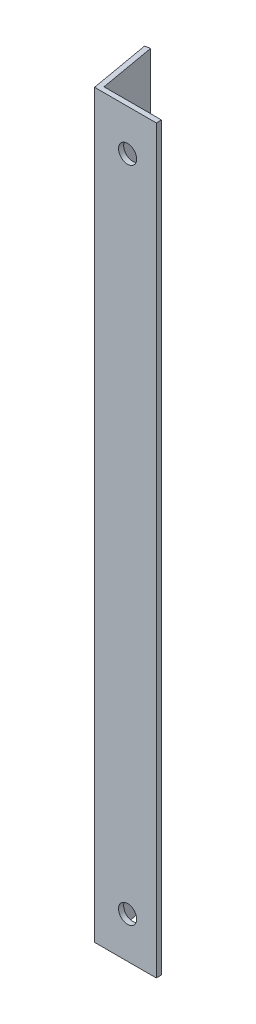
SolidWorks part; units mm, degrees
material "Galvanized Steel"
ref_plane "Front Plane" through (0, 0, 0) normal (0, 0, 1) x (1, 0, 0)
ref_plane "Top Plane" through (0, 0, 0) normal (0, 1, 0) x (1, 0, 0)
ref_plane "Right Plane" through (0, 0, 0) normal (1, 0, 0) x (0, 0, -1)
sketch "Sketch18" plane through (0, 0, 0) normal (0, 1, 0) x (1, 0, 0)
  line L0 (-3.4892, 38.0725) -> (2.6641, 3.175)
  line L1 (0, 0) -> (38.1, 0)
  line L2 (0, 0) -> (-6.616, 37.5212)
  line L3 (-6.616, 37.5212) -> (-3.4892, 38.0725)
  line L4 (38.1, 0) -> (38.1, 3.175)
  line L5 (2.6641, 3.175) -> (38.1, 3.175)
  point P1 (-2.1937, 38.928)
  point P8 (0, 0)
  point P9 (-4.1598, 38.0051)
  dimension "D1" = 38.1
  dimension "D2" = 3.175
  dimension "D3" = 100
extrude "Boss-Extrude1" add sketch "Sketch18" along normal mid plane 457.2
sketch "Sketch19" plane through (0, 0, -3.175) normal (0, 0, -1) x (-1, 0, 0)
  line L0 (-38.1, 228.6) -> (-2.6641, 228.6) construction
  circle A0 centre (-20.3821, 203.2) radius 5.588
  point P4 (-20.3821, 228.6)
  dimension "D1" = 11.176
  dimension "D3" = 203.2
extrude "Cut-Extrude2" cut sketch "Sketch19" against normal through all
mirror "Mirror1" about plane through (0, 0, 0) normal (0, 1, 0) of "Cut-Extrude2"
